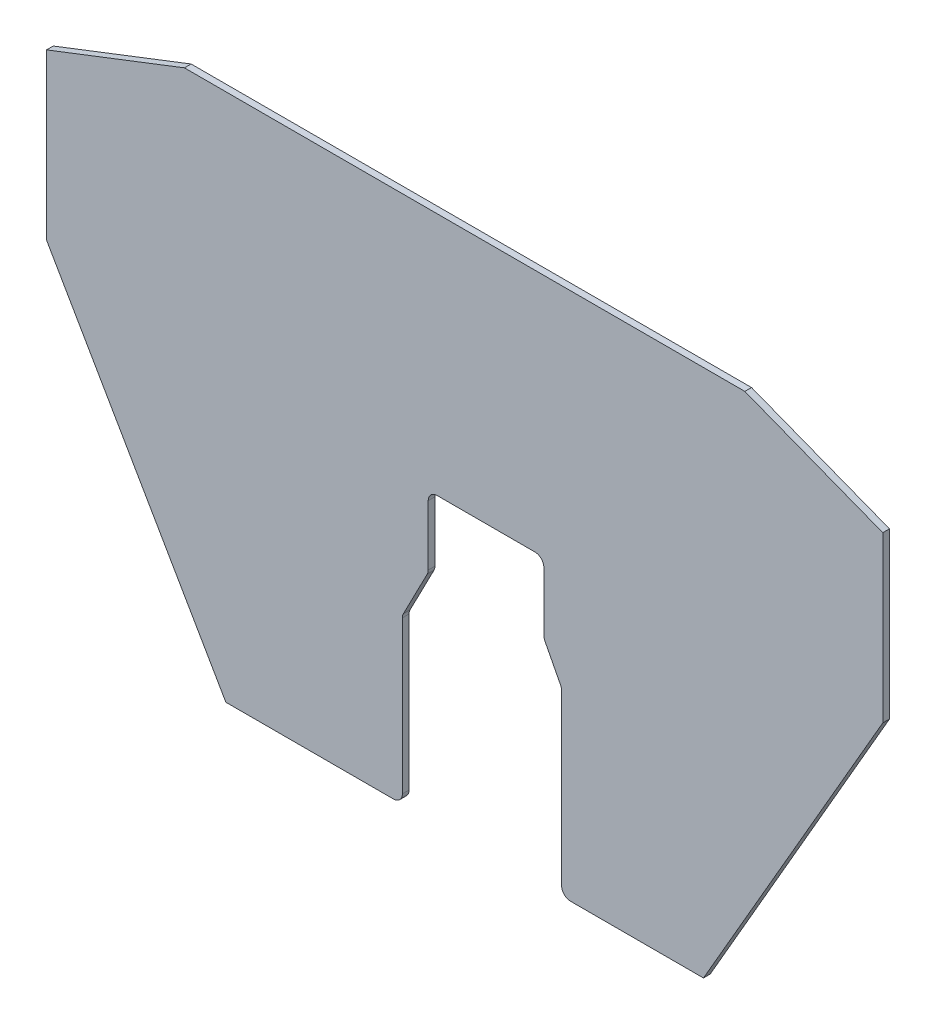
SolidWorks part; units mm, degrees
ref_plane "Front Plane" through (0, 0, 0) normal (0, 0, 1) x (1, 0, 0)
ref_plane "Top Plane" through (0, 0, 0) normal (0, 1, 0) x (1, 0, 0)
ref_plane "Right Plane" through (0, 0, 0) normal (1, 0, 0) x (0, 0, -1)
sketch "Sketch1" plane through (0, 0, 0) normal (0, 0, 1) x (1, 0, 0)
  line L0 (0, 205.7814) -> (0, -171.6157) construction
  line L1 (170.4677, -171.6157) -> (69.2396, -171.6157)
  line L2 (298.45, 50.0562) -> (298.45, 167.6814)
  line L3 (200.025, 205.7814) -> (63.5, 205.7814)
  line L4 (-298.45, 50.0562) -> (-298.45, 167.6814)
  line L5 (282.9448, -195.0905) -> (-298.45, 205.7814) construction
  line L6 (298.45, 205.7814) -> (-296.0019, -204.0934) construction
  line L7 (177.8, -158.9157) -> (-177.8, -158.9157) construction
  line L8 (-170.4677, -171.6157) -> (-298.45, 50.0562)
  line L9 (170.4677, -171.6157) -> (298.45, 50.0562)
  line L10 (-63.5, 205.7814) -> (-200.025, 205.7814)
  line L11 (-63.5, 205.7814) -> (63.5, 205.7814)
  line L12 (-63.5, -171.6157) -> (-170.4677, -171.6157)
  line L13 (-44.45, -54.8862) -> (-44.45, -171.6157)
  line L14 (50.8, 31.5843) -> (56.5396, 31.5843)
  line L15 (-298.45, 167.6814) -> (-200.025, 205.7814)
  line L16 (-44.45, -171.6157) -> (-63.5, -171.6157)
  line L17 (63.5, -19.2157) -> (-63.5, -171.6157) construction
  line L18 (63.5, -171.6157) -> (-63.5, -19.2157) construction
  line L19 (50.8, 31.5843) -> (-26.0104, 31.5843)
  line L20 (298.45, 167.6814) -> (200.025, 205.7814)
  line L21 (56.5396, 31.5843) -> (56.5396, -18.4436)
  line L22 (-26.0104, 31.5843) -> (-26.0104, -19.2157)
  line L23 (50.8, 31.5843) -> (-50.8, -19.2157) construction
  line L24 (50.8, -19.2157) -> (-50.8, 31.5843) construction
  line L25 (-26.0104, -19.2157) -> (-44.45, -54.8862)
  line L26 (56.5396, -18.4436) -> (69.2396, -43.0112)
  line L27 (69.2396, -43.0112) -> (69.2396, -171.6157)
  point P0 (0, 0)
  point P11 (0, -158.9157)
  point P15 (0, 155.9882)
  point P17 (0, -95.4157)
  point P23 (0, 6.1843)
  point P28 (-38.1, 31.5843)
  point P29 (-63.5, -43.7833)
  point P30 (63.5, -43.7833)
  point P31 (-38.1, -19.2157)
  dimension "D1" = 596.9
  dimension "D2" = 127
  dimension "D3" = 355.6
  dimension "D4" = 12.7
  dimension "D5" = 120
  dimension "D6" = 377.3971
  dimension "D7" = 152.4
  dimension "D8" = 82.55
  dimension "D9" = 50.8
  dimension "D10" = 98.425
  dimension "D11" = 38.1
extrude "Boss-Extrude1" add sketch "Sketch1" along normal blind 4.7752
fillet "Fillet1" radius 6.35 8 edges at (-26.0104, 31.5843, 2.3876) (-26.0104, -19.2157, 2.3876) (-44.45, -54.8862, 2.3876) (-44.45, -171.6157, 2.3876) (69.2396, -171.6157, 2.3876) (69.2396, -43.0112, 2.3876) (56.5396, -18.4436, 2.3876) (56.5396, 31.5843, 2.3876)
sketch "Sketch2" plane through (0, 0, 4.7752) normal (0, 0, 1) x (1, 0, 0)
  line L0 (-200.025, 193.0814) -> (200.025, 193.0814) construction
  line L1 (-200.025, 205.7814) -> (200.025, 205.7814)
  line L2 (-200.025, 205.7814) -> (-200.025, 180.3814)
  line L3 (-200.025, 180.3814) -> (200.025, 180.3814)
  line L4 (200.025, 205.7814) -> (200.025, 180.3814)
  line L5 (0, 205.7814) -> (0, 180.3814) construction
  dimension "D1" = 25.4
